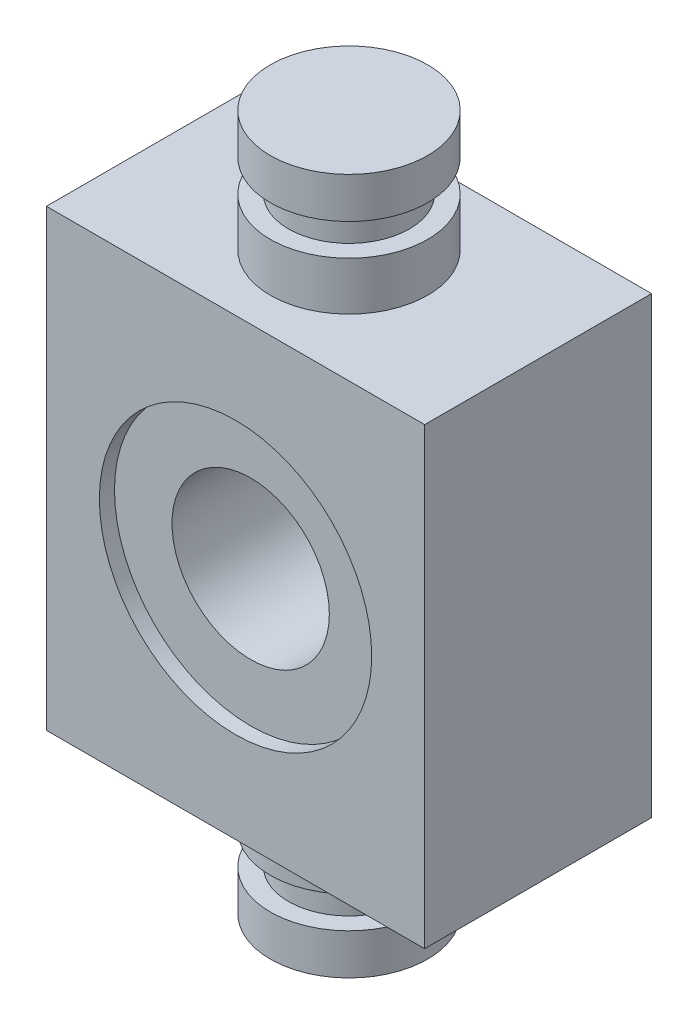
SolidWorks part; units mm, degrees
ref_plane "Front Plane" through (0, 0, 0) normal (1, 0, 0) x (0, 1, 0)
ref_plane "Top Plane" through (0, 0, 0) normal (0, 0, 1) x (0, 1, 0)
ref_plane "Right Plane" through (0, 0, 0) normal (0, 1, 0) x (-1, 0, 0)
sketch "Sketch1" plane through (0, 0, 0) normal (0, 0, 1) x (0, 1, 0)
  line L0 (-137.8743, 0) -> (132.485, 0) construction
  line L1 (0, 137.2006) -> (0, -135.4042) construction
  line L3 (-75, 62.5) -> (75, 62.5)
  line L4 (-75, 62.5) -> (-75, -62.5)
  line L5 (-75, -62.5) -> (75, -62.5)
  line L6 (75, 62.5) -> (75, -62.5)
  dimension "D1" = 150
  dimension "D2" = 125
extrude "Boss-Extrude1" add sketch "Sketch1" along normal mid plane 75
sketch "Sketch2" plane through (0, 0, 37.5) normal (0, 0, 1) x (1, 0, 0)
  circle A0 centre (0, 0) radius 45
  dimension "D1" = 90
extrude "Cut-Extrude1" cut sketch "Sketch2" against normal blind 5 and the other way through all
sketch "Sketch3" plane through (0, 0, 32.5) normal (0, 0, 1) x (1, 0, 0)
  circle A0 centre (0, 0) radius 26
  dimension "D1" = 52
extrude "Cut-Extrude2" cut sketch "Sketch3" against normal up to next
sketch "Sketch4" plane through (0, 75, 0) normal (0, 1, 0) x (-1, 0, 0)
  circle A0 centre (0, 0) radius 26
  dimension "D1" = 52
extrude "Boss-Extrude2" add sketch "Sketch4" along normal blind 16
sketch "Sketch5" plane through (0, 91, 0) normal (0, 1, 0) x (-1, 0, 0)
  circle A0 centre (0, 0) radius 20
  dimension "D1" = 40
extrude "Boss-Extrude3" add sketch "Sketch5" along normal blind 10.5
sketch "Sketch6" plane through (0, 101.5, 0) normal (0, 1, 0) x (-1, 0, 0)
  circle A0 centre (0, 0) radius 26
  dimension "D1" = 52
extrude "Boss-Extrude4" add sketch "Sketch6" along normal blind 13.5
mirror "Mirror1" about plane through (0, 0, 0) normal (0, 1, 0) of "Boss-Extrude2", "Boss-Extrude3", "Boss-Extrude4"
